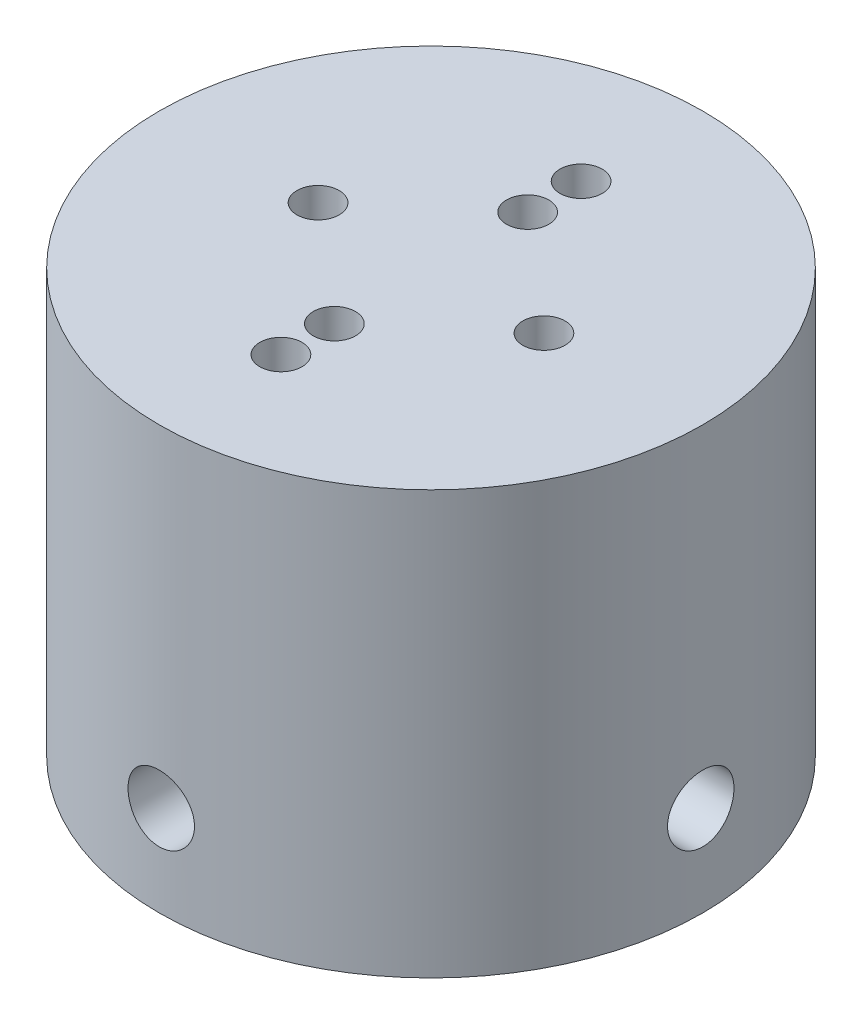
SolidWorks part; units mm, degrees
ref_plane "Plan de face" through (0, 0, 0) normal (0, 0, 1) x (1, 0, 0)
ref_plane "Plan de dessus" through (0, 0, 0) normal (0, 1, 0) x (1, 0, 0)
ref_plane "Plan de droite" through (0, 0, 0) normal (1, 0, 0) x (0, 0, -1)
sketch "Sketch1" plane through (0, 0, 0) normal (0, 1, 0) x (1, 0, 0)
  circle A0 centre (0, 0) radius 22.5
  dimension "D1" = 45
extrude "Boss-Extrude1" add sketch "Sketch1" along normal mid plane 35
sketch "Sketch2" plane through (0, -17.5, 0) normal (0, -1, 0) x (1, 0, 0)
  circle A0 centre (0, 0) radius 17.5
  circle A1 centre (0, 0) radius 22.5 construction
  dimension "D1" = 5
extrude "Cut-Extrude1" cut sketch "Sketch2" against normal blind 25
sketch "Sketch3" plane through (0, 0, 0) normal (1, 0, 0) x (0, 0, -1)
  line L0 (-22.5, -17.5) -> (22.5, -17.5) construction
  circle A0 centre (0, -10) radius 2.75
  point P2 (0, 0)
  dimension "D1" = 5.5
  dimension "D2" = 7.5
extrude "Cut-Extrude2" cut sketch "Sketch3" against normal through all both and the other way through all
sketch "Sketch4" plane through (0, 0, 0) normal (0, 0, 1) x (1, 0, 0)
  line L0 (-22.5, -17.5) -> (22.5, -17.5) construction
  circle A0 centre (0, -10) radius 2.75
  dimension "D1" = 5.5
  dimension "D2" = 7.5
extrude "Cut-Extrude3" cut sketch "Sketch4" against normal through all both and the other way through all
sketch "Sketch5" plane through (0, 17.5, 0) normal (0, 1, 0) x (1, 0, 0)
  line L0 (0, 22.5) -> (0, -22.5) construction
  line L1 (-22.5, 0) -> (22.5, 0) construction
  circle A0 centre (0, 0) radius 9.35 construction
  circle A1 centre (0, 0) radius 8 construction
  circle A2 centre (0, 0) radius 12.425 construction
  circle A3 centre (0, 12.425) radius 1.75
  circle A4 centre (0, 8) radius 1.75
  circle A5 centre (0, 0) radius 22.5 construction
  circle A6 centre (0, -8) radius 1.75
  circle A7 centre (0, -12.425) radius 1.75
  circle A8 centre (-9.35, 0) radius 1.75
  circle A9 centre (9.35, 0) radius 1.75
  dimension "D1" = 18.7
  dimension "D2" = 16
  dimension "D3" = 24.85
  dimension "D4" = 3.5
  dimension "D5" = 3.5
  dimension "D6" = 3.5
  dimension "D7" = 3.5
extrude "Cut-Extrude4" cut sketch "Sketch5" against normal blind 10
